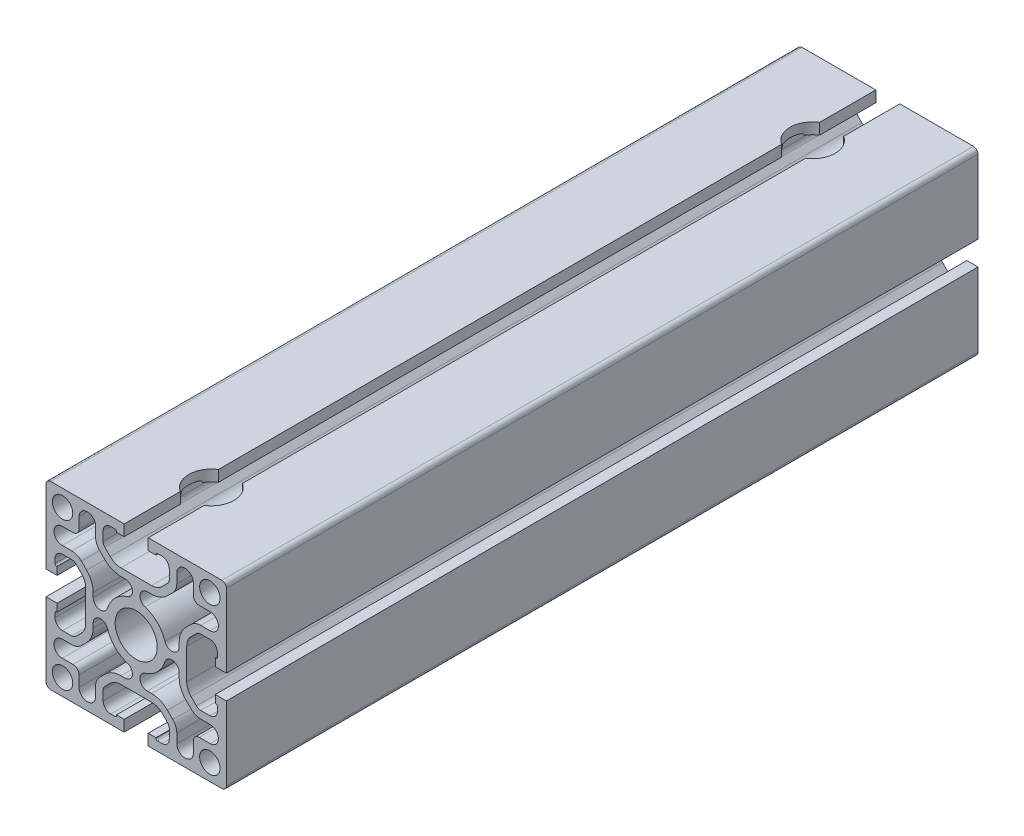
SolidWorks part; units mm, degrees
ref_plane "Płaszczyzna przednia" through (0, 0, 0) normal (0, 0, 1) x (1, 0, 0)
ref_plane "Płaszczyzna górna" through (0, 0, 0) normal (0, 1, 0) x (1, 0, 0)
ref_plane "Płaszczyzna prawa" through (0, 0, 0) normal (1, 0, 0) x (0, 0, -1)
ref_plane "Plane1" through (0, 0, 0) normal (0, 0, -1) x (-1, 0, 0)
sketch "Sketch1" plane through (0, 0, 0) normal (0, 0, -1) x (-1, 0, 0)
  line L0 (5.1034, -14.3) -> (3.6784, -14.3)
  line L1 (14.3, -3.6784) -> (14.3, -5.1134)
  line L2 (16.4818, -10.4017) -> (18.2431, -12.173)
  line L3 (21.434, -13.5) -> (24.6, -13.5)
  line L4 (24.6, -19) -> (21, -19)
  line L5 (19, -21) -> (19, -24.6)
  line L6 (13.5, -24.6) -> (13.5, -21.454)
  line L7 (12.182, -18.272) -> (10.4067, -16.4967)
  line L8 (-3.6784, -14.3) -> (-5.1034, -14.3)
  line L9 (-10.4067, -16.4967) -> (-12.182, -18.272)
  line L10 (-13.5, -21.454) -> (-13.5, -24.6)
  line L11 (-19, -24.6) -> (-19, -21)
  line L12 (-21, -19) -> (-24.6, -19)
  line L13 (-24.6, -13.5) -> (-21.434, -13.5)
  line L14 (-18.2431, -12.173) -> (-16.4818, -10.4017)
  line L15 (-14.3, -5.1134) -> (-14.3, -3.6784)
  line L16 (-5.1034, 14.3) -> (-3.6784, 14.3)
  line L17 (-14.3, 3.6784) -> (-14.3, 5.1134)
  line L18 (-16.4818, 10.4017) -> (-18.2431, 12.173)
  line L19 (-21.434, 13.5) -> (-24.6, 13.5)
  line L20 (-24.6, 19) -> (-21, 19)
  line L21 (-19, 21) -> (-19, 24.6)
  line L22 (-13.5, 24.6) -> (-13.5, 21.454)
  line L23 (-12.182, 18.272) -> (-10.4067, 16.4967)
  line L24 (3.6784, 14.3) -> (5.1034, 14.3)
  line L25 (10.4067, 16.4967) -> (12.182, 18.272)
  line L26 (13.5, 21.454) -> (13.5, 24.6)
  line L27 (19, 24.6) -> (19, 21)
  line L28 (21, 19) -> (24.6, 19)
  line L29 (24.6, 13.5) -> (21.434, 13.5)
  line L30 (18.2431, 12.173) -> (16.4818, 10.4017)
  line L31 (14.3, 5.1134) -> (14.3, 3.6784)
  line L32 (5.1, 16.8) -> (-5.11, 16.8)
  line L33 (-8.6455, 18.2645) -> (-10.42, 20.04)
  line L34 (-11, 21.45) -> (-11, 24.5)
  line L35 (-8.5, 27) -> (-7.07, 27)
  line L36 (-6.57, 26.5) -> (-6.57, 26.3)
  line L37 (-6.57, 26.3) -> (-4, 26.3)
  line L38 (-4, 26.3) -> (-4, 30)
  line L39 (-4, 30) -> (-28.5, 30)
  line L40 (-30, 28.5) -> (-30, 4)
  line L41 (-30, 4) -> (-26.3, 4)
  line L42 (-26.3, 4) -> (-26.3, 6.57)
  line L43 (-26.3, 6.57) -> (-26.5, 6.57)
  line L44 (-27, 7.07) -> (-27, 8.5)
  line L45 (-24.5, 11) -> (-21.45, 11)
  line L46 (-20.0358, 10.4142) -> (-18.27, 8.65)
  line L47 (-16.8, 5.11) -> (-16.8, -5.1)
  line L48 (-18.2645, -8.6355) -> (-20.04, -10.41)
  line L49 (-21.45, -11) -> (-24.5, -11)
  line L50 (-27, -8.5) -> (-27, -7.07)
  line L51 (-26.5, -6.57) -> (-26.3, -6.57)
  line L52 (-26.3, -6.57) -> (-26.3, -4)
  line L53 (-26.3, -4) -> (-30, -4)
  line L54 (-30, -4) -> (-30, -28.5)
  line L55 (-28.5, -30) -> (-4, -30)
  line L56 (-4, -30) -> (-4, -26.3)
  line L57 (-4, -26.3) -> (-6.57, -26.3)
  line L58 (-6.57, -26.3) -> (-6.57, -26.5)
  line L59 (-7.07, -27) -> (-8.5, -27)
  line L60 (-11, -24.5) -> (-11, -21.45)
  line L61 (-10.4142, -20.0358) -> (-8.65, -18.26)
  line L62 (-5.11, -16.8) -> (5.1, -16.8)
  line L63 (8.64, -18.26) -> (10.41, -20.03)
  line L64 (11, -21.45) -> (11, -24.5)
  line L65 (8.5, -27) -> (7.07, -27)
  line L66 (6.57, -26.5) -> (6.57, -26.3)
  line L67 (6.57, -26.3) -> (4, -26.3)
  line L68 (4, -26.3) -> (4, -30)
  line L69 (4, -30) -> (28.5, -30)
  line L70 (30, -28.5) -> (30, -4)
  line L71 (30, -4) -> (26.3, -4)
  line L72 (26.3, -4) -> (26.3, -6.57)
  line L73 (26.3, -6.57) -> (26.5, -6.57)
  line L74 (27, -7.07) -> (27, -8.5)
  line L75 (24.5, -11) -> (21.45, -11)
  line L76 (20.0358, -10.4142) -> (18.26, -8.64)
  line L77 (16.8, -5.1) -> (16.8, 5.11)
  line L78 (18.26, 8.65) -> (20.0358, 10.4142)
  line L79 (21.45, 11) -> (24.5, 11)
  line L80 (27, 8.5) -> (27, 7.07)
  line L81 (26.5, 6.57) -> (26.3, 6.57)
  line L82 (26.3, 6.57) -> (26.3, 4)
  line L83 (26.3, 4) -> (30, 4)
  line L84 (30, 4) -> (30, 28.5)
  line L85 (28.5, 30) -> (4, 30)
  line L86 (4, 30) -> (4, 26.3)
  line L87 (4, 26.3) -> (6.57, 26.3)
  line L88 (6.57, 26.3) -> (6.57, 26.5)
  line L89 (7.07, 27) -> (8.5, 27)
  line L90 (11, 24.5) -> (11, 21.45)
  line L91 (10.4142, 20.0358) -> (8.64, 18.27)
  circle A0 centre (-24.5, 24.5) radius 3.4
  circle A1 centre (24.5, 24.5) radius 3.4
  circle A2 centre (-24.5, -24.49) radius 3.4
  circle A3 centre (24.5, -24.49) radius 3.4
  circle A4 centre (0, 0) radius 7
  arc A5 (3.6784, -14.3) -> (2.9597, -9.552) centre (3.6784, -11.8716) cw
  arc A6 (2.9597, -9.552) -> (9.552, -2.9597) centre (0, 0) ccw
  arc A7 (9.552, -2.9597) -> (14.3, -3.6784) centre (11.8716, -3.6784) cw
  arc A8 (14.3, -5.1134) -> (16.4818, -10.4017) centre (21.8, -5.1134) ccw
  arc A9 (18.2431, -12.173) -> (21.434, -13.5) centre (21.434, -9) ccw
  arc A10 (24.6, -13.5) -> (24.6, -19) centre (24.6, -16.25) cw
  arc A11 (21, -19) -> (19, -21) centre (21, -21) ccw
  arc A12 (19, -24.6) -> (13.5, -24.6) centre (16.25, -24.6) cw
  arc A13 (13.5, -21.454) -> (12.182, -18.272) centre (9, -21.454) ccw
  arc A14 (10.4067, -16.4967) -> (5.1034, -14.3) centre (5.1034, -21.8) ccw
  arc A15 (-9.552, -2.9597) -> (-2.9597, -9.552) centre (0, 0) ccw
  arc A16 (-2.9597, -9.552) -> (-3.6784, -14.3) centre (-3.6784, -11.8716) cw
  arc A17 (-5.1034, -14.3) -> (-10.4067, -16.4967) centre (-5.1034, -21.8) ccw
  arc A18 (-12.182, -18.272) -> (-13.5, -21.454) centre (-9, -21.454) ccw
  arc A19 (-13.5, -24.6) -> (-19, -24.6) centre (-16.25, -24.6) cw
  arc A20 (-19, -21) -> (-21, -19) centre (-21, -21) ccw
  arc A21 (-24.6, -19) -> (-24.6, -13.5) centre (-24.6, -16.25) cw
  arc A22 (-21.434, -13.5) -> (-18.2431, -12.173) centre (-21.434, -9) ccw
  arc A23 (-16.4818, -10.4017) -> (-14.3, -5.1134) centre (-21.8, -5.1134) ccw
  arc A24 (-14.3, -3.6784) -> (-9.552, -2.9597) centre (-11.8716, -3.6784) cw
  arc A25 (-3.6784, 14.3) -> (-2.9597, 9.552) centre (-3.6784, 11.8716) cw
  arc A26 (-2.9597, 9.552) -> (-9.552, 2.9597) centre (0, 0) ccw
  arc A27 (-9.552, 2.9597) -> (-14.3, 3.6784) centre (-11.8716, 3.6784) cw
  arc A28 (-14.3, 5.1134) -> (-16.4818, 10.4017) centre (-21.8, 5.1134) ccw
  arc A29 (-18.2431, 12.173) -> (-21.434, 13.5) centre (-21.434, 9) ccw
  arc A30 (-24.6, 13.5) -> (-24.6, 19) centre (-24.6, 16.25) cw
  arc A31 (-21, 19) -> (-19, 21) centre (-21, 21) ccw
  arc A32 (-19, 24.6) -> (-13.5, 24.6) centre (-16.25, 24.6) cw
  arc A33 (-13.5, 21.454) -> (-12.182, 18.272) centre (-9, 21.454) ccw
  arc A34 (-10.4067, 16.4967) -> (-5.1034, 14.3) centre (-5.1034, 21.8) ccw
  arc A35 (9.552, 2.9597) -> (2.9597, 9.552) centre (0, 0) ccw
  arc A36 (2.9597, 9.552) -> (3.6784, 14.3) centre (3.6784, 11.8716) cw
  arc A37 (5.1034, 14.3) -> (10.4067, 16.4967) centre (5.1034, 21.8) ccw
  arc A38 (12.182, 18.272) -> (13.5, 21.454) centre (9, 21.454) ccw
  arc A39 (13.5, 24.6) -> (19, 24.6) centre (16.25, 24.6) cw
  arc A40 (19, 21) -> (21, 19) centre (21, 21) ccw
  arc A41 (24.6, 19) -> (24.6, 13.5) centre (24.6, 16.25) cw
  arc A42 (21.434, 13.5) -> (18.2431, 12.173) centre (21.434, 9) ccw
  arc A43 (16.4818, 10.4017) -> (14.3, 5.1134) centre (21.8, 5.1134) ccw
  arc A44 (14.3, 3.6784) -> (9.552, 2.9597) centre (11.8716, 3.6784) cw
  arc A45 (-5.11, 16.8) -> (-8.6455, 18.2645) centre (-5.11, 21.8) cw
  arc A46 (-10.42, 20.04) -> (-11, 21.45) centre (-8.9925, 21.4515) cw
  arc A47 (-11, 24.5) -> (-8.5, 27) centre (-8.5, 24.5) cw
  arc A48 (-7.07, 27) -> (-6.57, 26.5) centre (-7.07, 26.5) cw
  arc A49 (-28.5, 30) -> (-30, 28.5) centre (-28.5, 28.5) ccw
  arc A50 (-26.5, 6.57) -> (-27, 7.07) centre (-26.5, 7.07) cw
  arc A51 (-27, 8.5) -> (-24.5, 11) centre (-24.5, 8.5) cw
  arc A52 (-21.45, 11) -> (-20.0358, 10.4142) centre (-21.45, 9) cw
  arc A53 (-18.27, 8.65) -> (-16.8, 5.11) centre (-21.7951, 5.111) cw
  arc A54 (-16.8, -5.1) -> (-18.2645, -8.6355) centre (-21.8, -5.1) cw
  arc A55 (-20.04, -10.41) -> (-21.45, -11) centre (-21.4424, -9.0384) cw
  arc A56 (-24.5, -11) -> (-27, -8.5) centre (-24.5, -8.5) cw
  arc A57 (-27, -7.07) -> (-26.5, -6.57) centre (-26.5, -7.07) cw
  arc A58 (-30, -28.5) -> (-28.5, -30) centre (-28.5, -28.5) ccw
  arc A59 (-6.57, -26.5) -> (-7.07, -27) centre (-7.07, -26.5) cw
  arc A60 (-8.5, -27) -> (-11, -24.5) centre (-8.5, -24.5) cw
  arc A61 (-11, -21.45) -> (-10.4142, -20.0358) centre (-9, -21.45) cw
  arc A62 (-8.65, -18.26) -> (-5.11, -16.8) centre (-5.1017, -21.8418) cw
  arc A63 (5.1, -16.8) -> (8.64, -18.26) centre (5.0917, -21.8418) cw
  arc A64 (10.41, -20.03) -> (11, -21.45) centre (8.9927, -21.4515) cw
  arc A65 (11, -24.5) -> (8.5, -27) centre (8.5, -24.5) cw
  arc A66 (7.07, -27) -> (6.57, -26.5) centre (7.07, -26.5) cw
  arc A67 (28.5, -30) -> (30, -28.5) centre (28.5, -28.5) ccw
  arc A68 (26.5, -6.57) -> (27, -7.07) centre (26.5, -7.07) cw
  arc A69 (27, -8.5) -> (24.5, -11) centre (24.5, -8.5) cw
  arc A70 (21.45, -11) -> (20.0358, -10.4142) centre (21.45, -9) cw
  arc A71 (18.26, -8.64) -> (16.8, -5.1) centre (21.8418, -5.0917) cw
  arc A72 (16.8, 5.11) -> (18.26, 8.65) centre (21.8418, 5.1017) cw
  arc A73 (20.0358, 10.4142) -> (21.45, 11) centre (21.45, 9) cw
  arc A74 (24.5, 11) -> (27, 8.5) centre (24.5, 8.5) cw
  arc A75 (27, 7.07) -> (26.5, 6.57) centre (26.5, 7.07) cw
  arc A76 (30, 28.5) -> (28.5, 30) centre (28.5, 28.5) ccw
  arc A77 (6.57, 26.5) -> (7.07, 27) centre (7.0699, 26.5001) cw
  arc A78 (8.5, 27) -> (11, 24.5) centre (8.5, 24.5) cw
  arc A79 (11, 21.45) -> (10.4142, 20.0358) centre (9, 21.45) cw
  arc A80 (8.64, 18.27) -> (5.1, 16.8) centre (5.101, 21.7951) cw
extrude "Boss-Extrude1" add sketch "Sketch1" against normal blind 250
sketch "Sketch2" plane through (0, 0, 0) normal (0, 1, 0) x (1, 0, 0)
  line L0 (4, -250) -> (28.5, -250) construction
  line L1 (-28.5, 0) -> (-4, 0) construction
  line L2 (-30, -250) -> (-30, 0) construction
  circle A0 centre (0, -25) radius 7.5
  circle A1 centre (0, -225) radius 7.5
  dimension "D5" = 15
  dimension "D6" = 15
  dimension "D1" = 25
  dimension "D2" = 25
  dimension "D3" = 30
  dimension "D4" = 30
extrude "Cut-Extrude1" cut sketch "Sketch2" along normal through all both and the other way through all
